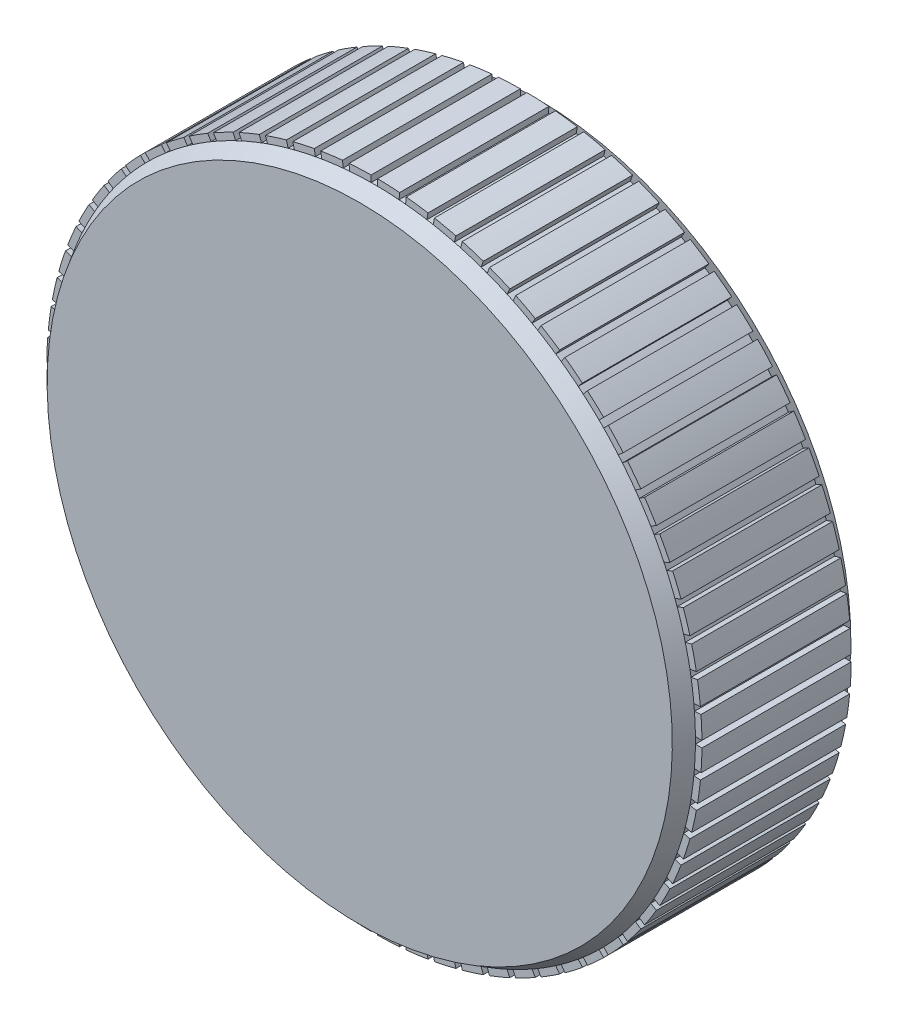
SolidWorks part; units mm, degrees
ref_plane "Front" through (0, 0, 0) normal (0, 0, 1) x (1, 0, 0)
ref_plane "Top" through (0, 0, 0) normal (0, 1, 0) x (1, 0, 0)
ref_plane "Right" through (0, 0, 0) normal (1, 0, 0) x (0, 0, -1)
sketch "Sketch20" plane through (0, 0, 0) normal (1, 0, 0) x (0, 0, -1)
  line L2 (0, 12.7) -> (0, -12.7) construction
  line L3 (-7.9375, 12.7) -> (-7.9375, -12.7) construction
  point P11 (0, 0)
  dimension "Head Height" = 7.9375
  dimension "Head Diameter" = 25.4
sketch "Sketch1" plane through (0, 0, 0) normal (0, 0, 1) x (1, 0, 0)
  circle A0 centre (0, 0) radius 3.175
  dimension "dia" = 6.35
extrude "Extrude1" add sketch "Sketch1" along normal blind 3.175
sketch "Sketch21" plane through (0, 0, 0) normal (0, 0, 1) x (1, 0, 0)
  line L0 (-12.7, 0) -> (12.7, 0) construction
  line L1 (-12.7, 1.5875) -> (12.7, 1.5875) construction
  line L2 (0, 0) -> (0, 1.5875) construction
  circle A0 centre (0, 0) radius 12.7
  dimension "D1" = 1.5875
extrude "Boss-Extrude1" add sketch "Sketch21" along normal up to vertex (7.9375 mm away) up to point (0, -12.7, 7.9375)
sketch "Sketch34" plane through (0, 0, 0) normal (0, 0, -1) x (-1, 0, 0)
  circle A0 centre (0, 0) radius 7.1438
  circle A1 centre (0, 0) radius 12.7
  circle A2 centre (0, 0) radius 12.7 construction
  dimension "D1" = 14.2875
extrude "Cut-Extrude4" cut sketch "Sketch34" against normal blind 1.016
ref_plane "Plane1" through (0, 12.7, 0) normal (0, 1, 0) x (-1, 0, 0)
sketch "Sketch22" plane through (0, 12.7, 0) normal (0, 1, 0) x (-1, 0, 0)
  line L0 (0, 7.9375) -> (0, 0) construction
  line L1 (-0.127, 7.9375) -> (0.127, 7.9375)
  line L3 (-0.127, 7.9375) -> (-0.127, 0)
  line L4 (-0.127, 0) -> (0.127, 0)
  line L7 (0.127, 7.9375) -> (0.127, 0)
  dimension "D1" = 0.254
extrude "Cut-Extrude1" cut sketch "Sketch22" against normal offset from surface (0.2546 mm away) 0.254
pattern_circular "CirPattern1" count 72 over 360 about axis through (0, 0, 0) along (0, 0, 1) of "Cut-Extrude1"
sketch "Sketch29" plane through (0, 0, 0) normal (1, 0, 0) x (0, 0, -1)
  line L0 (-7.3705, 12.446) -> (-7.9375, 12.1187)
  line L1 (-7.9375, 12.1187) -> (-7.9375, 12.954)
  line L2 (-7.3705, 12.446) -> (-7.3705, 12.954)
  line L3 (-7.9375, 12.954) -> (-7.3705, 12.954)
  line L5 (0, 0) -> (-4.4767, 0) construction
  line L6 (-7.9375, 12.7) -> (-1.016, 12.7) construction
  line L7 (-4.4767, 12.7) -> (-4.4767, 0) construction
  line L8 (-1.016, 12.954) -> (-1.583, 12.954)
  line L9 (-1.583, 12.446) -> (-1.583, 12.954)
  line L10 (-1.016, 12.1187) -> (-1.016, 12.954)
  line L11 (-1.583, 12.446) -> (-1.016, 12.1187)
  line L26 (-1.016, 11.9769) -> (-1.016, 12.2338) construction
  dimension "D1" = 0.254
  dimension "D2" = 30
  dimension "D3" = 0.254
  dimension "D4" = 0.567
revolve "Cut-Revolve1" cut sketch "Sketch29" angle 360 about L5
chamfer "Chamfer3" distance 0.381 angle 45 1 edges at (-7.1438, 0, 0)
sketch "Sketch35" plane through (0, 0, 0) normal (0, 0, 1) x (1, 0, 0)
  circle A0 centre (0, 0) radius 4.7625
  circle A1 centre (0, 0) radius 2.413
  dimension "D1" = 9.525
  dimension "D2" = 4.826
extrude "Cut-Extrude5" cut sketch "Sketch35" along normal offset from surface (5.3975 mm away) 2.54 up to face at (0, 12.1187, 7.9375)
sketch "Sketch36" plane through (0, 0, 0) normal (0, 0, -1) x (-1, 0, 0)
  circle A1 centre (0, 0) radius 2.413
  circle A2 centre (0, 0) radius 2.413
  dimension "D1" = 0
extrude "Cut-Extrude6" cut sketch "Sketch36" against normal offset from surface (3.8735 mm away) 1.524 up to face at (2.413, 0, 5.3975)
equation "\"D4@Sketch29\" = \"Head Height@Sketch20\"/14"
